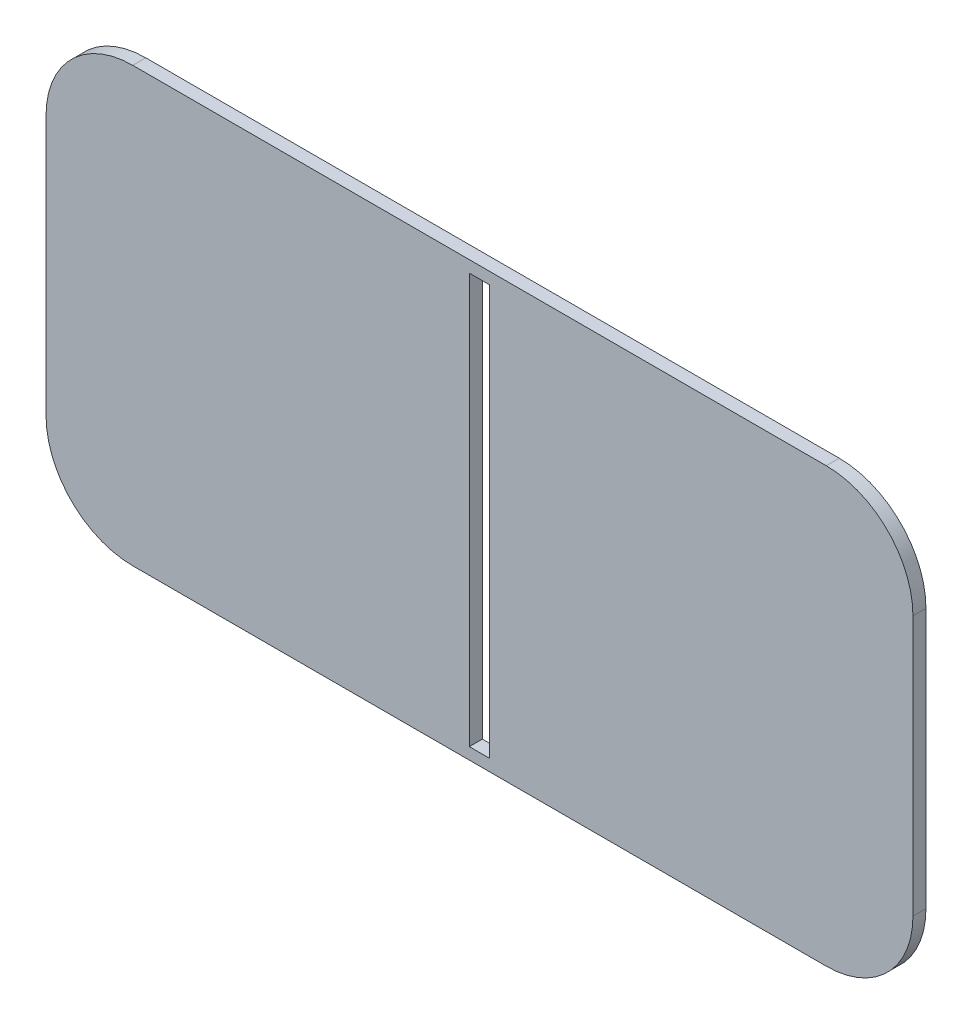
SolidWorks part; units mm, degrees
ref_plane "Front Plane" through (0, 0, 0) normal (0, 0, 1) x (1, 0, 0)
ref_plane "Top Plane" through (0, 0, 0) normal (0, 1, 0) x (1, 0, 0)
ref_plane "Right Plane" through (0, 0, 0) normal (1, 0, 0) x (0, 0, -1)
sketch "Sketch2" plane through (0, 0, 0) normal (0, 0, 1) x (1, 0, 0)
  line L0 (96.2346, 2.0198) -> (96.2346, -97.9802)
  line L1 (16.2346, 2.0198) -> (176.2346, 2.0198)
  line L2 (-3.7654, -17.9802) -> (-3.7654, -77.9802)
  line L3 (16.2346, -97.9802) -> (176.2346, -97.9802)
  line L4 (196.2346, -17.9802) -> (196.2346, -77.9802)
  line L6 (93.8856, -0.6785) -> (98.5837, -0.6785)
  line L7 (93.8856, -0.6785) -> (93.8856, -95.2819)
  line L8 (93.8856, -95.2819) -> (98.5837, -95.2819)
  line L9 (98.5837, -0.6785) -> (98.5837, -95.2819)
  line L10 (93.8856, -0.6785) -> (98.5837, -95.2819) construction
  line L11 (93.8856, -95.2819) -> (98.5837, -0.6785) construction
  arc A0 (-3.7654, -77.9802) -> (16.2346, -97.9802) centre (16.2346, -77.9802) ccw
  arc A1 (176.2346, -97.9802) -> (196.2346, -77.9802) centre (176.2346, -77.9802) ccw
  arc A2 (176.2346, 2.0198) -> (196.2346, -17.9802) centre (176.2346, -17.9802) cw
  arc A3 (16.2346, 2.0198) -> (-3.7654, -17.9802) centre (16.2346, -17.9802) ccw
  point P0 (96.2346, -47.9802)
  point P2 (96.2346, -47.9802)
extrude "Boss-Extrude2" add sketch "Sketch2" along normal blind 3 contours L1 A3 L2 A0 L3 L0 | A2 L1 L0 L3 A1 L4
